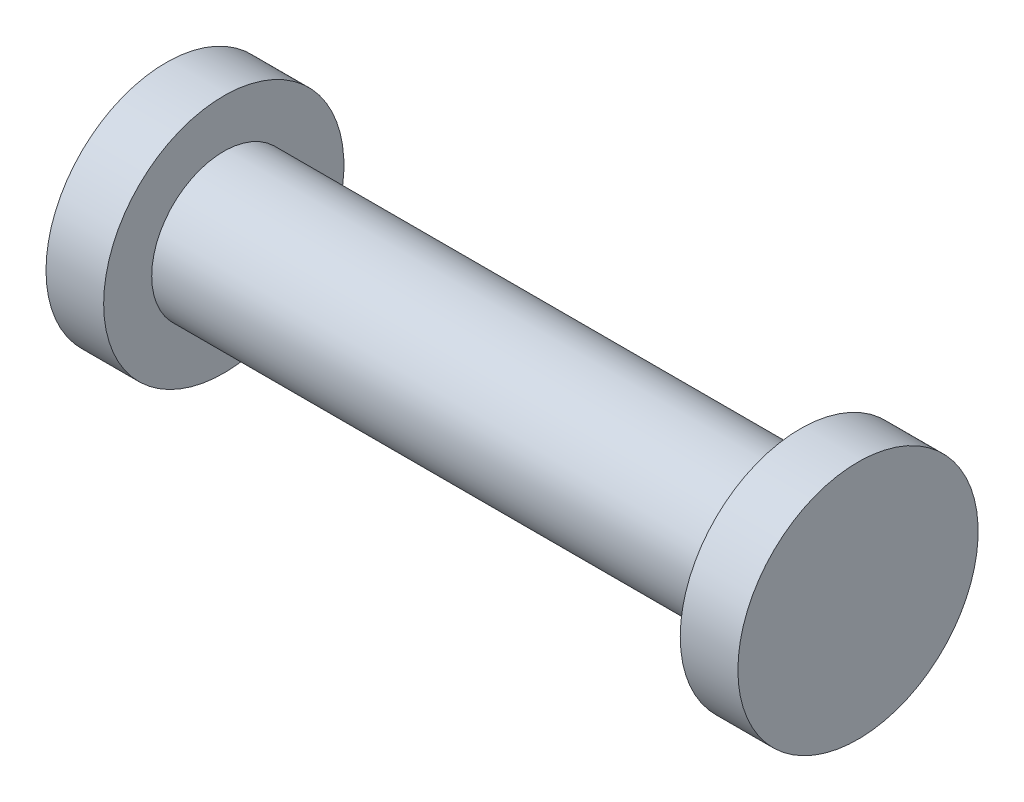
SolidWorks part; units mm, degrees
material "Plain Carbon Steel"
ref_plane "Front Plane" through (0, 0, 0) normal (0, 0, 1) x (1, 0, 0)
ref_plane "Top Plane" through (0, 0, 0) normal (0, 1, 0) x (1, 0, 0)
ref_plane "Right Plane" through (0, 0, 0) normal (1, 0, 0) x (0, 0, -1)
sketch "Sketch1" plane through (0, 0, 0) normal (0, 1, 0) x (1, 0, 0)
  line L0 (0, 0) -> (66.7152, 0) construction
  line L1 (0, 7.5) -> (0, 0) construction
  line L9 (36, 0) -> (-36, 0)
  line L10 (-36, 0) -> (-36, 12.5)
  line L11 (-36, 12.5) -> (-30, 12.5)
  line L12 (-30, 12.5) -> (-30, 7.5)
  line L13 (-30, 7.5) -> (30, 7.5)
  line L14 (30, 7.5) -> (30, 12.5)
  line L15 (30, 12.5) -> (36, 12.5)
  line L16 (36, 12.5) -> (36, 0)
  dimension "D1" = 60
  dimension "D2" = 6
  dimension "D3" = 12.5
  dimension "D4" = 7.5
revolve "Revolve2" add sketch "Sketch1" angle 360 about L0
